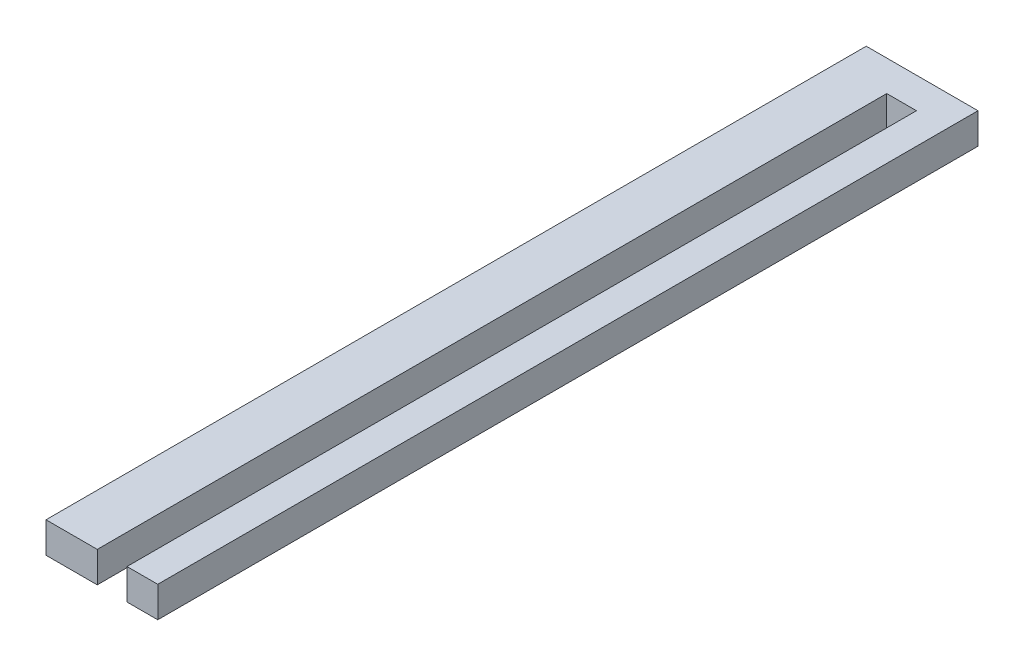
SolidWorks part; units mm, degrees
ref_plane "前视基准面" through (0, 0, 0) normal (0, 0, 1) x (1, 0, 0)
ref_plane "上视基准面" through (0, 0, 0) normal (0, 1, 0) x (1, 0, 0)
ref_plane "右视基准面" through (0, 0, 0) normal (1, 0, 0) x (0, 0, -1)
other "Configuration Table"
sketch "草图1" plane through (0, 0, 0) normal (0, 1, 0) x (1, 0, 0)
  line L0 (0, 0) -> (0, 80)
  line L1 (0, 80) -> (10.9, 80)
  line L2 (10.9, 80) -> (10.9, 0)
  line L3 (10.9, 0) -> (7.9, 0)
  line L4 (7.9, 0) -> (7.9, 77)
  line L5 (7.9, 77) -> (5, 77)
  line L6 (5, 77) -> (5, 0)
  line L7 (5, 0) -> (0, 0)
  dimension "D1" = 2.9
  dimension "D2" = 5
  dimension "D3" = 3
  dimension "D4" = 3
  dimension "D5" = 80
extrude "凸台-拉伸1" add sketch "草图1" along normal blind 3
